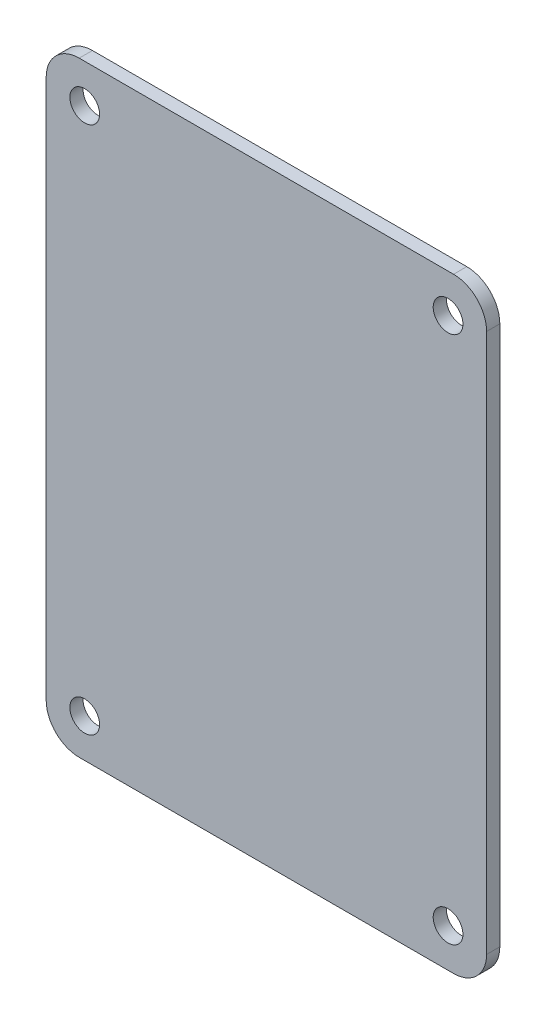
SolidWorks part; units mm, degrees
material "ABS"
ref_plane "Front Plane" through (0, 0, 0) normal (0, 0, 1) x (1, 0, 0)
ref_plane "Top Plane" through (0, 0, 0) normal (0, 1, 0) x (1, 0, 0)
ref_plane "Right Plane" through (0, 0, 0) normal (1, 0, 0) x (0, 0, -1)
sketch "Sketch1" plane through (0, 0, 0) normal (0, 0, 1) x (1, 0, 0)
  line L0 (-1000, 0) -> (49000, 0) construction
  line L1 (-17, -27.5) -> (17, -27.5)
  line L2 (-20, -24.5) -> (-20, 24.5)
  line L3 (-17, 27.5) -> (17, 27.5)
  line L4 (20, -24.5) -> (20, 24.5)
  line L5 (-20, -27.5) -> (20, 27.5) construction
  line L6 (-20, 27.5) -> (20, -27.5) construction
  line L7 (0, -1000) -> (0, 49000) construction
  circle A0 centre (-16.5, 24) radius 1.35
  circle A1 centre (-16.5, -24) radius 1.35
  circle A2 centre (16.5, -24) radius 1.35
  circle A3 centre (16.5, 24) radius 1.35
  arc A4 (-20, -24.5) -> (-17, -27.5) centre (-17, -24.5) ccw
  arc A5 (17, -27.5) -> (20, -24.5) centre (17, -24.5) ccw
  arc A6 (17, 27.5) -> (20, 24.5) centre (17, 24.5) cw
  arc A7 (-20, 24.5) -> (-17, 27.5) centre (-17, 24.5) cw
  point P0 (0, 0)
  dimension "D3" = 33
  dimension "D5" = 2.7
  dimension "D6" = 3
  dimension "D1" = 55
  dimension "D2" = 40
  dimension "D4" = 48
extrude "Boss-Extrude1" add sketch "Sketch1" along normal mid plane 1.2
